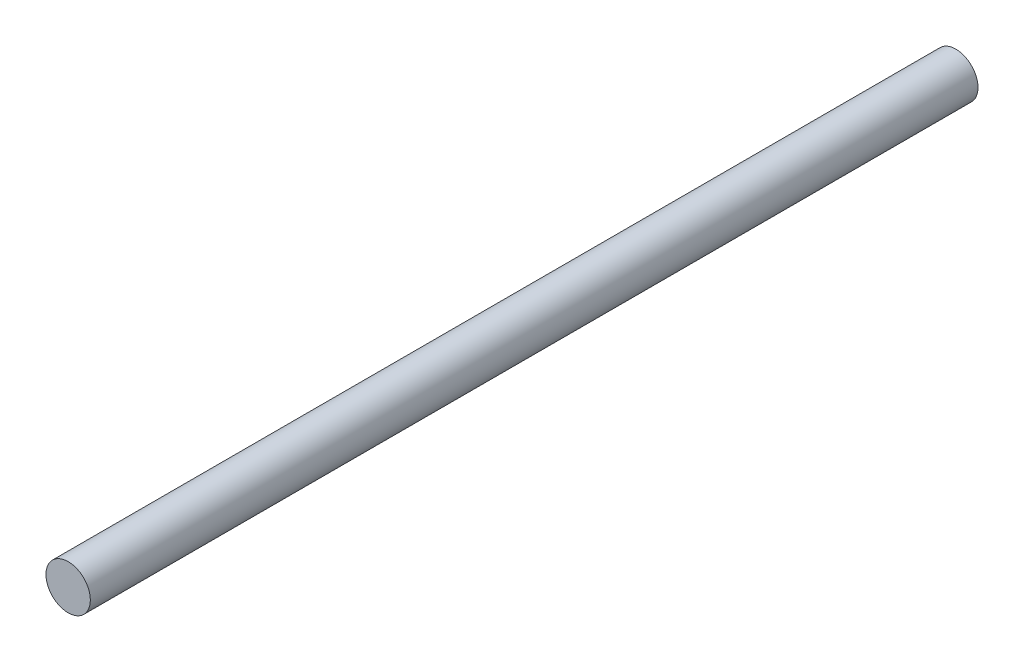
SolidWorks part; units mm, degrees
ref_plane "Front Plane" through (0, 0, 0) normal (0, 0, 1) x (1, 0, 0)
ref_plane "Top Plane" through (0, 0, 0) normal (0, 1, 0) x (1, 0, 0)
ref_plane "Right Plane" through (0, 0, 0) normal (1, 0, 0) x (0, 0, -1)
sketch "Sketch2" plane through (0, 0, 0) normal (0, 0, 1) x (1, 0, 0)
  circle A0 centre (0, 0) radius 2.5
  dimension "D1" = 5
extrude "Boss-Extrude1" add sketch "Sketch2" along normal blind 100
